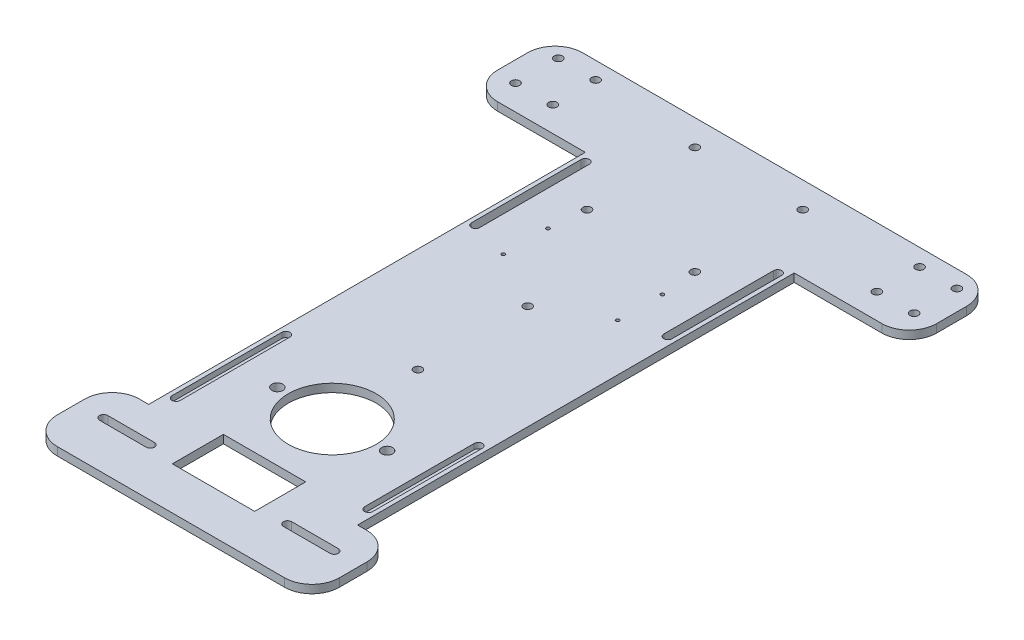
SolidWorks part; units mm, degrees
material "Acrylic (Medium-high impact)"
ref_plane "Front Plane" through (0, 0, 0) normal (0, 0, 1) x (1, 0, 0)
ref_plane "Top Plane" through (0, 0, 0) normal (0, 1, 0) x (1, 0, 0)
ref_plane "Right Plane" through (0, 0, 0) normal (1, 0, 0) x (0, 0, -1)
sketch "Sketch1" plane through (0, 0, 0) normal (0, 1, 0) x (1, 0, 0)
  line L1 (-80, -110) -> (80, -110)
  line L2 (-80, -110) -> (-80, 110)
  line L3 (-80, 110) -> (80, 110)
  line L4 (80, -110) -> (80, 110)
  line L5 (0, 110) -> (0, -110) construction
  line L6 (-80, 0) -> (80, 0) construction
  point P0 (0, 0)
  dimension "D1" = 160
  dimension "D2" = 220
extrude "Boss-Extrude1" add sketch "Sketch1" along normal blind 3
sketch "Sketch3" plane through (0, 3, 0) normal (0, 1, 0) x (1, 0, 0)
  line L0 (-80, 110) -> (-80, 80) construction
  line L1 (-80, 110) -> (-80, -110) construction
  line L2 (-80, 80) -> (-53.65, 80) construction
  line L3 (-53.65, 80) -> (-53.65, 110) construction
  line L4 (80, 110) -> (-80, 110) construction
  line L5 (-53.65, 110) -> (-80, 110) construction
  line L6 (0, 110) -> (0, -110) construction
  line L7 (-80, -110) -> (80, -110) construction
  line L8 (-66.825, 110) -> (-66.825, 80) construction
  line L9 (-53.65, 95) -> (-80, 95) construction
  line L10 (53.65, 95) -> (80, 95) construction
  line L11 (66.825, 110) -> (66.825, 80) construction
  line L16 (53.65, 110) -> (80, 110) construction
  line L17 (53.65, 80) -> (53.65, 110) construction
  line L18 (80, 80) -> (53.65, 80) construction
  line L19 (80, 110) -> (80, 80) construction
  circle A2 centre (-59.03, 88.2) radius 1.5
  circle A9 centre (-72.63, 88.2) radius 1.5
  circle A12 centre (-59.03, 103.8) radius 1.5
  circle A13 centre (-72.63, 103.8) radius 1.5
  circle A14 centre (72.63, 103.8) radius 1.5
  circle A15 centre (59.03, 103.8) radius 1.5
  circle A16 centre (72.63, 88.2) radius 1.5
  circle A17 centre (59.03, 88.2) radius 1.5
  dimension "D3" = 7.795
  dimension "D4" = 3
  dimension "D7" = 3
  dimension "D9" = 3
  dimension "D1" = 30
  dimension "D2" = 26.35
  dimension "D5" = 13.6
  dimension "D6" = 5.38
  dimension "D8" = 15.6
  dimension "D10" = 13.6
extrude "Cut-Extrude1" cut sketch "Sketch3" against normal blind 3
sketch "Sketch4" plane through (0, 3, 0) normal (0, 1, 0) x (1, 0, 0)
  line L0 (0, 102.5842) -> (0, 0) construction
  line L1 (-21.65, 59.2842) -> (21.65, 59.2842) construction
  line L2 (-21.65, 59.2842) -> (-21.65, 102.5842) construction
  line L3 (-21.65, 102.5842) -> (21.65, 102.5842) construction
  line L4 (21.65, 59.2842) -> (21.65, 102.5842) construction
  line L5 (0, 102.5842) -> (0, 59.2842) construction
  line L6 (-21.65, 80.9342) -> (21.65, 80.9342) construction
  circle A0 centre (-19.65, 100.5842) radius 1.5
  circle A1 centre (19.65, 100.5842) radius 1.5
  circle A2 centre (19.65, 61.2842) radius 1.5
  circle A3 centre (-19.65, 61.2842) radius 1.5
  point P0 (0, 80.9342)
  dimension "D3" = 3
  dimension "D1" = 43.3
  dimension "D2" = 43.3
  dimension "D4" = 2
  dimension "D5" = 2
extrude "Cut-Extrude2" cut sketch "Sketch4" against normal blind 3
sketch "Sketch5" plane through (0, 3, 0) normal (0, 1, 0) x (1, 0, 0)
  line L1 (-38, -31) -> (38, -31) construction
  line L2 (-38, -31) -> (-38, 31) construction
  line L3 (-38, 31) -> (38, 31) construction
  line L4 (38, -31) -> (38, 31) construction
  line L5 (0, 31) -> (0, -31) construction
  line L6 (-38, 0) -> (38, 0) construction
  circle A0 centre (0, 20) radius 1.5
  circle A1 centre (0, -20) radius 1.5
  point P0 (0, 0)
  dimension "D3" = 3
  dimension "D4" = 3
  dimension "D1" = 76
  dimension "D2" = 62
  dimension "D5" = 20
  dimension "D6" = 20
extrude "Cut-Extrude3" cut sketch "Sketch5" against normal blind 3
sketch "Sketch6" plane through (0, 3, 0) normal (0, 1, 0) x (1, 0, 0)
  line L0 (0, 49.0041) -> (0, -49.0041) construction
  line L1 (-21.59, 31.2241) -> (21.59, 31.2241) construction
  line L2 (-21.59, 31.2241) -> (-21.59, 49.0041) construction
  line L3 (-21.59, 49.0041) -> (21.59, 49.0041) construction
  line L4 (21.59, 31.2241) -> (21.59, 49.0041) construction
  line L6 (-21.59, 40.1141) -> (21.59, 40.1141) construction
  circle A0 centre (-20.83, 48.2441) radius 0.635
  circle A1 centre (20.83, 48.2441) radius 0.635
  circle A2 centre (20.83, 31.9841) radius 0.635
  circle A3 centre (-20.83, 31.9841) radius 0.635
  point P0 (0, 40.1141)
  dimension "D3" = 1.27
  dimension "D1" = 17.78
  dimension "D2" = 43.18
  dimension "D4" = 0.76
  dimension "D5" = 0.76
extrude "Cut-Extrude4" cut sketch "Sketch6" against normal blind 3
sketch "Sketch7" plane through (0, 3, 0) normal (0, 1, 0) x (1, 0, 0)
  line L0 (-80, -110) -> (80, -110) construction
  line L2 (-48.5, -90) -> (48.5, -90) construction
  line L3 (-48.5, -90) -> (-48.5, -110) construction
  line L4 (-48.5, -110) -> (48.5, -110) construction
  line L5 (48.5, -90) -> (48.5, -110) construction
  line L6 (0, -110) -> (0, -90) construction
  line L7 (-48.5, -100) -> (48.5, -100) construction
  line L8 (0, -110) -> (0, 0) construction
  line L9 (-42, -92.5) -> (-25, -92.5) construction
  line L10 (-42, -91) -> (-25, -91)
  line L11 (-42, -94) -> (-25, -94)
  line L12 (-15, -75.8799) -> (-15, -94.4875)
  line L13 (-15, -94.4875) -> (15, -94.4875)
  line L14 (15, -94.4875) -> (15, -75.8799)
  line L15 (15, -75.8799) -> (-15, -75.8799)
  line L16 (42, -92.5) -> (25, -92.5) construction
  line L17 (42, -91) -> (25, -91)
  line L18 (42, -94) -> (25, -94)
  arc A0 (-42, -91) -> (-42, -94) centre (-42, -92.5) ccw
  arc A1 (-25, -94) -> (-25, -91) centre (-25, -92.5) ccw
  arc A2 (42, -91) -> (42, -94) centre (42, -92.5) cw
  arc A3 (25, -94) -> (25, -91) centre (25, -92.5) cw
  point P0 (0, -100)
  point P9 (-33.5, -92.5)
  point P20 (33.5, -92.5)
  dimension "D4" = 1.5
  dimension "D1" = 97
  dimension "D2" = 20
  dimension "D3" = 17
  dimension "D5" = 3
  dimension "D6" = 2.5
  dimension "D7" = 6.5
  dimension "D8" = 15
  dimension "D9" = 15
extrude "Cut-Extrude5" cut sketch "Sketch7" against normal blind 3
sketch "Sketch8" plane through (0, 3, 0) normal (0, 1, 0) x (1, 0, 0)
  line L0 (58, -110) -> (58, 69.9534)
  line L1 (-80, -110) -> (80, -110) construction
  line L2 (58, 69.9534) -> (80, 69.9534)
  line L3 (80, -110) -> (80, 110) construction
  line L4 (80, -110) -> (58, -110)
  line L5 (0, 0) -> (0, -47.5032) construction
  line L6 (80, 69.9534) -> (80, -110)
  line L7 (-80, 69.9534) -> (-80, -110)
  line L8 (-80, -110) -> (-58, -110)
  line L9 (-58, 69.9534) -> (-80, 69.9534)
  line L10 (-58, -110) -> (-58, 69.9534)
  dimension "D1" = 22
extrude "Cut-Extrude6" cut sketch "Sketch8" against normal blind 3
sketch "Sketch10" plane through (0, 3, 0) normal (0, 1, 0) x (1, 0, 0)
  line L0 (0, -51.2062) -> (0, 0) construction
  line L1 (-24, -75.2062) -> (24, -75.2062) construction
  line L2 (-24, -75.2062) -> (-24, -27.2062) construction
  line L3 (-24, -27.2062) -> (24, -27.2062) construction
  line L4 (24, -75.2062) -> (24, -27.2062) construction
  line L5 (0, -27.2062) -> (0, -75.2062) construction
  line L6 (-24, -51.2062) -> (24, -51.2062) construction
  circle A0 centre (-20, -51.2062) radius 2
  circle A1 centre (20, -51.2062) radius 2
  dimension "D1" = 4
  dimension "D2" = 4
  dimension "D3" = 20
  dimension "D4" = 20
  dimension "D5" = 48
  dimension "D6" = 48
extrude "Cut-Extrude7" cut sketch "Sketch10" against normal blind 3
sketch "Sketch11" plane through (0, 3, 0) normal (0, 1, 0) x (1, 0, 0)
  line L0 (-80, 79.0636) -> (-38.0676, 79.0636)
  line L2 (-80, 110) -> (-80, 69.9534) construction
  line L3 (-38.0676, 79.0636) -> (-38.0676, -80.0397)
  line L4 (-38.0676, -80.0397) -> (-51.4076, -80.0397)
  line L5 (-51.4076, -80.0397) -> (-51.4076, -110)
  line L6 (-58, -110) -> (58, -110) construction
  line L7 (-51.4076, -110) -> (-58, -110)
  line L8 (-58, -110) -> (-58, 69.9534)
  line L9 (-58, -110) -> (-58, 69.9534) construction
  line L10 (-58, 69.9534) -> (-80, 69.9534) construction
  line L11 (-58, 69.9534) -> (-80, 69.9534)
  line L12 (-80, 69.9534) -> (-80, 79.0636)
  line L13 (0, 29.9335) -> (0, -12.6892) construction
  line L14 (80, 69.9534) -> (80, 79.0636)
  line L15 (58, 69.9534) -> (80, 69.9534)
  line L16 (58, -110) -> (58, 69.9534)
  line L17 (51.4076, -110) -> (58, -110)
  line L18 (51.4076, -80.0397) -> (51.4076, -110)
  line L19 (38.0676, -80.0397) -> (51.4076, -80.0397)
  line L20 (38.0676, 79.0636) -> (38.0676, -80.0397)
  line L21 (80, 79.0636) -> (38.0676, 79.0636)
extrude "Cut-Extrude8" cut sketch "Sketch11" against normal blind 3
fillet "Fillet1" radius 10 1 edges at (-51.4076, 1.5, 110)
fillet "Fillet2" radius 10 5 edges at (80, 1.5, -110) (80, 1.5, -79.0636) (-80, 1.5, -110) (-80, 1.5, -79.0636) (-51.4076, 1.5, 80.0397)
fillet "Fillet3" radius 10 2 edges at (51.4076, 1.5, 80.0397) (51.4076, 1.5, 110)
sketch "Sketch12" plane through (0, 3, 0) normal (0, 1, 0) x (1, 0, 0)
  line L0 (-35.0676, 36.0636) -> (-35.0676, 76.0636) construction
  line L1 (-36.5676, 36.0636) -> (-36.5676, 76.0636)
  line L2 (-33.5676, 36.0636) -> (-33.5676, 76.0636)
  line L3 (-38.0676, -80.0397) -> (-38.0676, 79.0636) construction
  line L4 (0, 20) -> (0, 76.8878) construction
  line L5 (35.0676, 36.0636) -> (35.0676, 76.0636) construction
  line L6 (36.5676, 36.0636) -> (36.5676, 76.0636)
  line L7 (33.5676, 36.0636) -> (33.5676, 76.0636)
  line L8 (-38.0676, 79.0636) -> (-70, 79.0636) construction
  arc A0 (-36.5676, 36.0636) -> (-33.5676, 36.0636) centre (-35.0676, 36.0636) ccw
  arc A1 (-33.5676, 76.0636) -> (-36.5676, 76.0636) centre (-35.0676, 76.0636) ccw
  arc A2 (36.5676, 36.0636) -> (33.5676, 36.0636) centre (35.0676, 36.0636) cw
  arc A3 (33.5676, 76.0636) -> (36.5676, 76.0636) centre (35.0676, 76.0636) cw
  point P2 (-35.0676, 56.0636)
  point P15 (35.0676, 56.0636)
  point P20 (-35.0676, 75.9643)
  dimension "D3" = 1.5
  dimension "D1" = 3
  dimension "D2" = 3
  dimension "D4" = 40
  dimension "D5" = 3
extrude "Cut-Extrude9" cut sketch "Sketch12" against normal blind 10
sketch "Sketch13" plane through (0, 3, 0) normal (0, 1, 0) x (1, 0, 0)
  line L0 (-20, -51.2062) -> (20, -51.2062) construction
  line L1 (0, -20) -> (0, -70.178) construction
  circle A0 centre (0, -51.2062) radius 16
  dimension "D2" = 32
  dimension "D1" = 40
extrude "Cut-Extrude10" cut sketch "Sketch13" against normal blind 10
sketch "Sketch14" plane through (0, 3, 0) normal (0, 1, 0) x (1, 0, 0)
  line L0 (-35.0676, -73.0397) -> (-35.0676, -33.0397) construction
  line L1 (-36.5676, -73.0397) -> (-36.5676, -33.0397)
  line L2 (-33.5676, -73.0397) -> (-33.5676, -33.0397)
  line L3 (-38.0676, -80.0397) -> (-38.0676, 79.0636) construction
  line L4 (-41.4076, -80.0397) -> (-38.0676, -80.0397) construction
  line L5 (0, 0) -> (0, -64.6728) construction
  line L6 (35.0676, -73.0397) -> (35.0676, -33.0397) construction
  line L7 (36.5676, -73.0397) -> (36.5676, -33.0397)
  line L8 (33.5676, -73.0397) -> (33.5676, -33.0397)
  arc A0 (-36.5676, -73.0397) -> (-33.5676, -73.0397) centre (-35.0676, -73.0397) ccw
  arc A1 (-33.5676, -33.0397) -> (-36.5676, -33.0397) centre (-35.0676, -33.0397) ccw
  arc A2 (36.5676, -73.0397) -> (33.5676, -73.0397) centre (35.0676, -73.0397) cw
  arc A3 (33.5676, -33.0397) -> (36.5676, -33.0397) centre (35.0676, -33.0397) cw
  point P2 (-35.0676, -53.0397)
  point P16 (35.0676, -53.0397)
  dimension "D5" = 1.5
  dimension "D1" = 3
  dimension "D2" = 3
  dimension "D3" = 7
  dimension "D4" = 40
extrude "Cut-Extrude11" cut sketch "Sketch14" against normal blind 2
